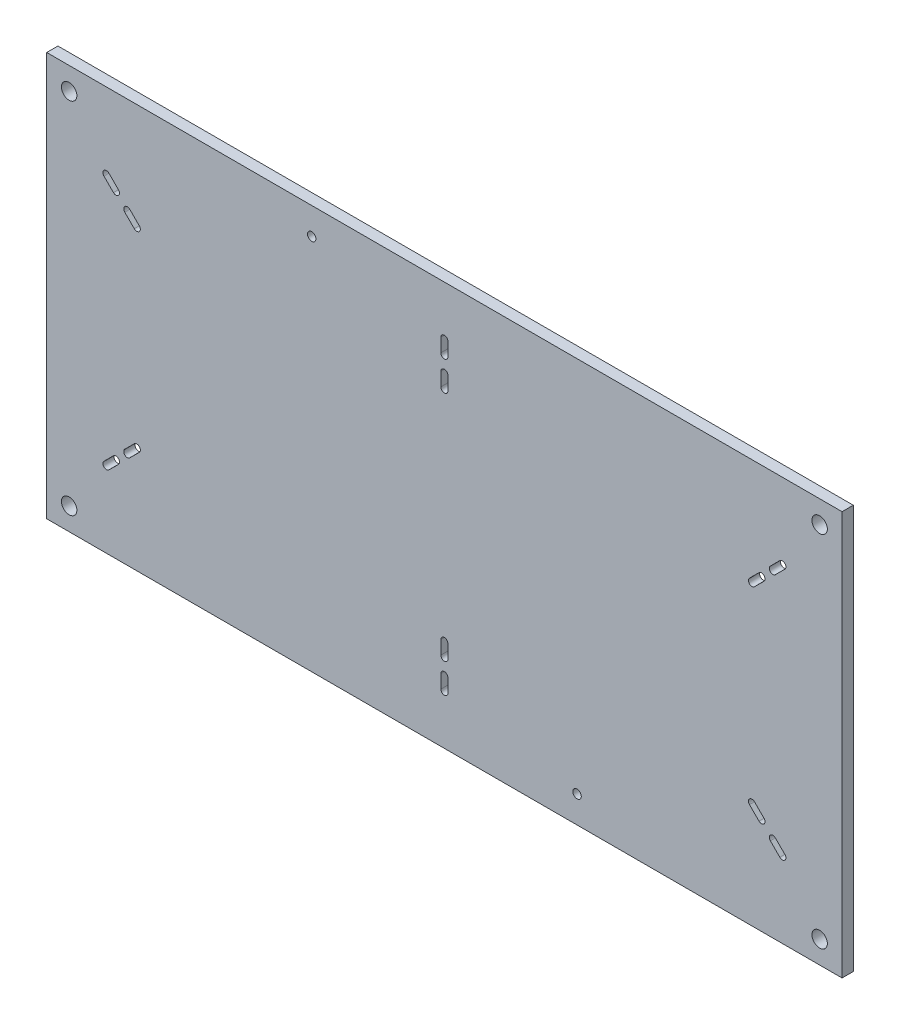
SolidWorks part; units mm, degrees
ref_plane "Front Plane" through (0, 0, 0) normal (0, 0, 1) x (1, 0, 0)
ref_plane "Top Plane" through (0, 0, 0) normal (0, 1, 0) x (1, 0, 0)
ref_plane "Right Plane" through (0, 0, 0) normal (1, 0, 0) x (0, 0, -1)
sketch "Sketch1" plane through (0, 0, 0) normal (0, 0, 1) x (1, 0, 0)
  line L1 (-225.1, 114.3) -> (225.1, 114.3)
  line L2 (-225.1, 114.3) -> (-225.1, -114.3)
  line L3 (-225.1, -114.3) -> (225.1, -114.3)
  line L4 (225.1, 114.3) -> (225.1, -114.3)
  line L5 (-225.1, 114.3) -> (225.1, -114.3) construction
  line L6 (-225.1, -114.3) -> (225.1, 114.3) construction
  point P0 (0, 0)
  dimension "D1" = 450.2
  dimension "D2" = 228.6
extrude "Boss-Extrude1" add sketch "Sketch1" along normal blind 6.35
sketch "Sketch3" plane through (0, 0, 6.35) normal (0, 0, 1) x (1, 0, 0)
  line L0 (-201.3161, -72.3408) -> (-192.3358, -81.3211)
  line L1 (-192.3358, -81.3211) -> (-161.803, -50.7882)
  line L2 (-161.803, -50.7882) -> (-170.7832, -41.808)
  line L3 (-170.7832, -41.808) -> (-201.3161, -72.3408)
  line L4 (-191.3028, -71.3078) -> (-185.9146, -65.9196) construction
  line L5 (-192.717, -69.8935) -> (-187.3288, -64.5054)
  line L6 (-189.8885, -72.722) -> (-184.5004, -67.3338)
  line L7 (-225.1, -114.3) -> (225.1, -114.3) construction
  line L8 (-174.1059, -54.1109) -> (-179.4941, -59.4991) construction
  line L9 (-172.6917, -55.5251) -> (-178.0799, -60.9133)
  line L10 (-225.1, 114.3) -> (-225.1, -114.3) construction
  line L11 (0, -106.7771) -> (0, 106.7771) construction
  line L24 (-175.5201, -52.6967) -> (-180.9083, -58.0849)
  line L25 (191.3028, -71.3078) -> (185.9146, -65.9196) construction
  line L28 (192.717, -69.8935) -> (187.3288, -64.5054)
  line L31 (189.8885, -72.722) -> (184.5004, -67.3338)
  line L34 (174.1059, -54.1109) -> (179.4941, -59.4991) construction
  line L37 (172.6917, -55.5251) -> (178.0799, -60.9133)
  line L40 (175.5201, -52.6967) -> (180.9083, -58.0849)
  line L43 (-170.7832, -50.7882) -> (-170.7832, -41.808)
  line L44 (-161.803, -50.7882) -> (-170.7832, -50.7882)
  line L45 (161.803, -50.7882) -> (170.7832, -50.7882)
  line L46 (170.7832, -50.7882) -> (170.7832, -41.808)
  line L47 (170.7832, -41.808) -> (201.3161, -72.3408)
  line L48 (161.803, -50.7882) -> (170.7832, -41.808)
  line L49 (192.3358, -81.3211) -> (161.803, -50.7882)
  line L50 (201.3161, -72.3408) -> (192.3358, -81.3211)
  line L51 (104.8793, 0) -> (-104.8793, 0) construction
  line L52 (-191.3028, 71.3078) -> (-185.9146, 65.9196) construction
  line L53 (-192.717, 69.8935) -> (-187.3288, 64.5054)
  line L54 (-189.8885, 72.722) -> (-184.5004, 67.3338)
  line L55 (-174.1059, 54.1109) -> (-179.4941, 59.4991) construction
  line L56 (-172.6917, 55.5251) -> (-178.0799, 60.9133)
  line L57 (-175.5201, 52.6967) -> (-180.9083, 58.0849)
  line L58 (191.3028, 71.3078) -> (185.9146, 65.9196) construction
  line L59 (192.717, 69.8935) -> (187.3288, 64.5054)
  line L60 (189.8885, 72.722) -> (184.5004, 67.3338)
  line L61 (174.1059, 54.1109) -> (179.4941, 59.4991) construction
  line L62 (172.6917, 55.5251) -> (178.0799, 60.9133)
  line L63 (175.5201, 52.6967) -> (180.9083, 58.0849)
  line L64 (201.3161, 72.3408) -> (192.3358, 81.3211)
  line L65 (192.3358, 81.3211) -> (161.803, 50.7882)
  line L66 (161.803, 50.7882) -> (170.7832, 41.808)
  line L67 (170.7832, 41.808) -> (201.3161, 72.3408)
  line L68 (170.7832, 50.7882) -> (170.7832, 41.808)
  line L69 (161.803, 50.7882) -> (170.7832, 50.7882)
  line L70 (-161.803, 50.7882) -> (-170.7832, 50.7882)
  line L71 (-170.7832, 50.7882) -> (-170.7832, 41.808)
  line L72 (-170.7832, 41.808) -> (-201.3161, 72.3408)
  line L73 (-161.803, 50.7882) -> (-170.7832, 41.808)
  line L74 (-192.3358, 81.3211) -> (-161.803, 50.7882)
  line L75 (-201.3161, 72.3408) -> (-192.3358, 81.3211)
  arc A0 (-192.717, -69.8935) -> (-189.8885, -72.722) centre (-191.3028, -71.3078) ccw
  arc A1 (-184.5004, -67.3338) -> (-187.3288, -64.5054) centre (-185.9146, -65.9196) ccw
  arc A2 (-172.6917, -55.5251) -> (-175.5201, -52.6967) centre (-174.1059, -54.1109) ccw
  arc A3 (-180.9083, -58.0849) -> (-178.0799, -60.9133) centre (-179.4941, -59.4991) ccw
  arc A4 (192.717, -69.8935) -> (189.8885, -72.722) centre (191.3028, -71.3078) cw
  arc A5 (184.5004, -67.3338) -> (187.3288, -64.5054) centre (185.9146, -65.9196) cw
  arc A6 (172.6917, -55.5251) -> (175.5201, -52.6967) centre (174.1059, -54.1109) cw
  arc A7 (180.9083, -58.0849) -> (178.0799, -60.9133) centre (179.4941, -59.4991) cw
  arc A8 (-192.717, 69.8935) -> (-189.8885, 72.722) centre (-191.3028, 71.3078) cw
  arc A9 (-184.5004, 67.3338) -> (-187.3288, 64.5054) centre (-185.9146, 65.9196) cw
  arc A10 (-172.6917, 55.5251) -> (-175.5201, 52.6967) centre (-174.1059, 54.1109) cw
  arc A11 (-180.9083, 58.0849) -> (-178.0799, 60.9133) centre (-179.4941, 59.4991) cw
  arc A12 (192.717, 69.8935) -> (189.8885, 72.722) centre (191.3028, 71.3078) ccw
  arc A13 (184.5004, 67.3338) -> (187.3288, 64.5054) centre (185.9146, 65.9196) ccw
  arc A14 (172.6917, 55.5251) -> (175.5201, 52.6967) centre (174.1059, 54.1109) ccw
  arc A15 (180.9083, 58.0849) -> (178.0799, 60.9133) centre (179.4941, 59.4991) ccw
  point P14 (188.6087, -68.6137)
  point P21 (176.8, -56.805)
  point P29 (-188.6087, -68.6137)
  point P36 (-176.8, -56.805)
  point P48 (-188.6087, 68.6137)
  point P55 (-176.8, 56.805)
  point P62 (188.6087, 68.6137)
  point P69 (176.8, 56.805)
  point P84 (-184.5004, -64.5054)
  point P85 (-180.9083, -60.9133)
  dimension "D6" = 2
  dimension "D10" = 5.08
  dimension "D9" = 4.699
  dimension "D1" = 43.18
  dimension "D2" = 12.7
  dimension "D3" = 57.495
  dimension "D4" = 48.3
  dimension "D7" = 7.62
  dimension "D8" = 6.35
extrude "Corner Slots" cut sketch "Sketch3" against normal blind 10 contours A11 L57 A10 L56 | A9 L54 A8 L53 | L60 A13 L59 A12 | L63 A15 L62 A14 | A5 L31 A4 L28 | A7 L40 A6 L37 | L9 A3 L24 A2 | L6 A1 L5 A0
hole_wizard "Foot Holes 1/4-20" positions "Sketch4" profile "Sketch5" hole size "1/4-20" standard "PEM® Inch" end condition through all
sketch "Sketch4" plane through (0, 0, 6.35) normal (0, 0, 1) x (1, 0, 0)
  line L0 (225.1, 114.3) -> (-225.1, 114.3) construction
  line L1 (-225.1, 114.3) -> (-225.1, -114.3) construction
  line L2 (-225.1, -114.3) -> (225.1, -114.3) construction
  point P0 (-212.4, 101.6)
  point P2 (-212.4, -101.6)
  dimension "D1" = 12.7
  dimension "D2" = 12.7
  dimension "D3" = 12.7
  dimension "D4" = 12.7
sketch "Sketch5" plane through (-212.4, 101.6, 6.35) normal (1, 0, 0) x (0, -1, 0)
  line L0 (0, 0) -> (0, 6.35)
  line L1 (0, 6.35) -> (4.3688, 6.35)
  line L2 (4.3688, 6.35) -> (4.3688, 0)
  line L5 (4.3688, 0) -> (0, 0)
  line L11 (0, -6.35) -> (0, 107.95) construction
  dimension "Thru Hole Dia." = 8.7376
  dimension "Thru Hole Depth" = 6.35
mirror "Mirror2" about plane through (0, 0, 0) normal (1, 0, 0) of "Foot Holes 1/4-20"
hole_wizard "ESD Fasterners" positions "Sketch6" profile "Sketch7" hole size "#6-32" standard "PEM® Inch" end condition through all
sketch "Sketch6" plane through (0, 0, 6.35) normal (0, 0, 1) x (1, 0, 0)
  line L0 (225.1, 114.3) -> (-225.1, 114.3) construction
  line L1 (-225.1, -114.3) -> (225.1, -114.3) construction
  line L2 (-225.1, 114.3) -> (-225.1, -114.3) construction
  line L3 (225.1, -114.3) -> (225.1, 114.3) construction
  point P0 (-75.1, 99.09)
  point P2 (75.1, -99.089)
  dimension "D1" = 15.21
  dimension "D2" = 15.211
  dimension "D3" = 150
  dimension "D4" = 150
sketch "Sketch7" plane through (-75.1, 99.09, 6.35) normal (1, 0, 0) x (0, -1, 0)
  line L0 (0, 0) -> (0, 6.35)
  line L1 (0, 6.35) -> (2.3812, 6.35)
  line L2 (2.3812, 6.35) -> (2.3812, 0)
  line L5 (2.3812, 0) -> (0, 0)
  line L11 (0, -6.35) -> (0, 107.95) construction
  dimension "Thru Hole Dia." = 4.7625
  dimension "Thru Hole Depth" = 6.35
sketch "Sketch16" plane through (0, 0, 0) normal (0, 0, 1) x (1, 0, 0)
  line L0 (0, -78.63) -> (0, -86.25) construction
  line L1 (2, -78.63) -> (2, -86.25)
  line L2 (-2, -78.63) -> (-2, -86.25)
  line L3 (-225.1, -114.3) -> (225.1, -114.3) construction
  line L4 (0, -69.55) -> (0, -61.93) construction
  line L7 (-2, -69.55) -> (-2, -61.93)
  line L8 (2, -69.55) -> (2, -61.93)
  line L9 (104.8793, 0) -> (-104.8793, 0) construction
  line L10 (0, 78.63) -> (0, 86.25) construction
  line L11 (2, 78.63) -> (2, 86.25)
  line L12 (-2, 78.63) -> (-2, 86.25)
  line L13 (0, 69.55) -> (0, 61.93) construction
  line L14 (-2, 69.55) -> (-2, 61.93)
  line L15 (2, 69.55) -> (2, 61.93)
  arc A0 (2, -78.63) -> (-2, -78.63) centre (0, -78.63) ccw
  arc A1 (-2, -86.25) -> (2, -86.25) centre (0, -86.25) ccw
  arc A4 (-2, -69.55) -> (2, -69.55) centre (0, -69.55) ccw
  arc A5 (2, -61.93) -> (-2, -61.93) centre (0, -61.93) ccw
  arc A6 (2, 78.63) -> (-2, 78.63) centre (0, 78.63) cw
  arc A7 (-2, 86.25) -> (2, 86.25) centre (0, 86.25) cw
  arc A8 (-2, 69.55) -> (2, 69.55) centre (0, 69.55) cw
  arc A9 (2, 61.93) -> (-2, 61.93) centre (0, 61.93) cw
  point P3 (0, -82.44)
  point P15 (0, -65.74)
  point P21 (0, 82.44)
  point P28 (0, 65.74)
  dimension "D1" = 31.86
  dimension "D2" = 2
  dimension "D5" = 9.08
  dimension "D3" = 7.62
  dimension "D4" = 2
extrude "Middle Slots" cut sketch "Sketch16" along normal blind 10
